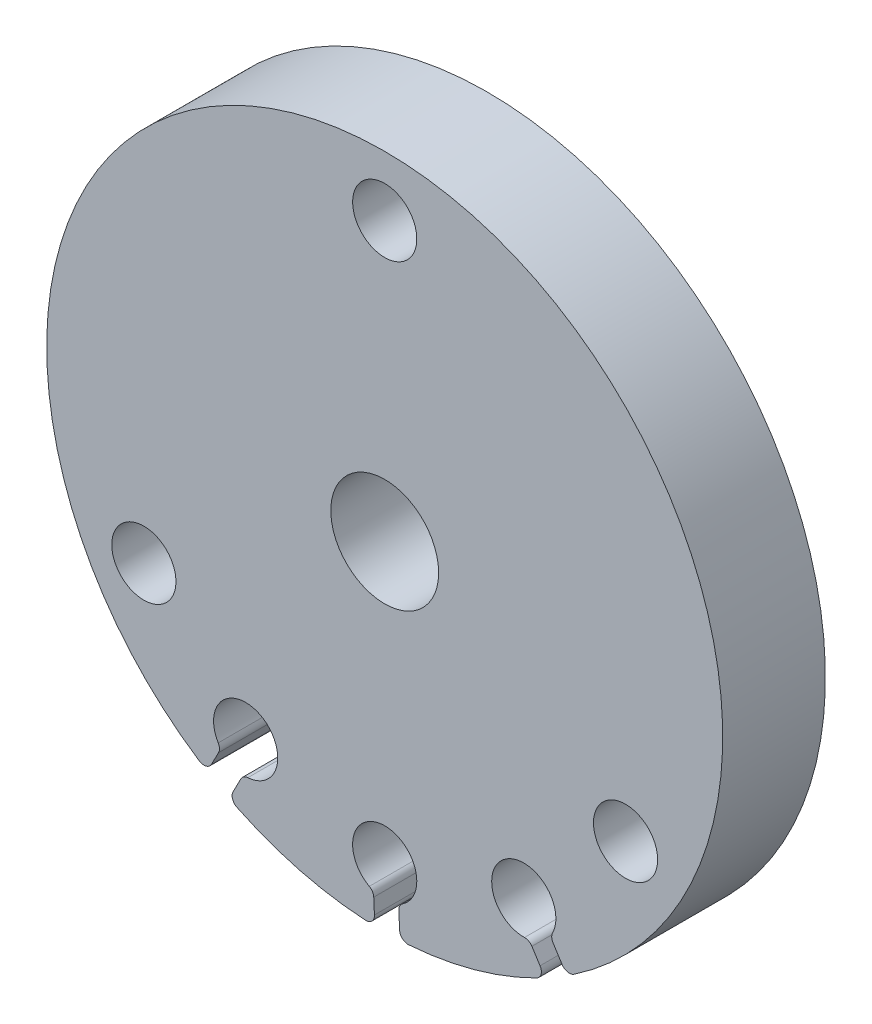
SolidWorks part; units mm, degrees
material "Полиэфирэфиркетон (ПЭЭК)"
ref_plane "Спереди" through (0, 0, 0) normal (0, 0, 1) x (1, 0, 0)
ref_plane "Сверху" through (0, 0, 0) normal (0, 1, 0) x (1, 0, 0)
ref_plane "Справа" through (0, 0, 0) normal (1, 0, 0) x (0, 0, -1)
sketch "Эскиз1" plane through (0, 0, 0) normal (0, 0, 1) x (1, 0, 0)
  circle A0 centre (0, 0) radius 19.75
  circle A1 centre (0, 0) radius 3.15
  dimension "D1" = 6.3
  dimension "D2" = 39.5
extrude "Бобышка-Вытянуть1" add sketch "Эскиз1" along normal blind 6
sketch "Эскиз2" plane through (0, 0, 0) normal (0, 0, -1) x (-1, 0, 0)
  line L0 (-10.9644, -17.1516) -> (-9.6728, -15.1312)
  line L2 (-8.4358, -15.922) -> (-9.6979, -17.8963)
  line L3 (-10.9644, -17.1516) -> (-9.6979, -17.8963)
  line L4 (-18.0712, -9.3715) -> (-15.9425, -8.2676) [skipped]
  line L5 (-18.0712, -9.3715) -> (-17.3468, -10.6497) [skipped]
  line L6 (-15.2666, -9.571) -> (-17.3468, -10.6497) [skipped]
  line L8 (-20.3359, 0.9196) -> (-17.9404, 0.8113) [skipped]
  line L9 (-20.3359, 0.9196) -> (-20.3476, -0.5495) [skipped]
  line L10 (-18.0067, -0.6554) -> (-20.3476, -0.5495) [skipped]
  line L12 (-17.1516, 10.9644) -> (-15.1312, 9.6728) [skipped]
  line L13 (-17.1516, 10.9644) -> (-17.8963, 9.6979) [skipped]
  line L14 (-15.922, 8.4358) -> (-17.8963, 9.6979) [skipped]
  line L16 (-9.3715, 18.0712) -> (-8.2676, 15.9425) [skipped]
  line L17 (-9.3715, 18.0712) -> (-10.6497, 17.3468) [skipped]
  line L18 (-9.571, 15.2666) -> (-10.6497, 17.3468) [skipped]
  line L20 (0.9196, 20.3359) -> (0.8113, 17.9404) [skipped]
  line L21 (0.9196, 20.3359) -> (-0.5495, 20.3476) [skipped]
  line L22 (-0.6554, 18.0067) -> (-0.5495, 20.3476) [skipped]
  line L24 (10.9644, 17.1516) -> (9.6728, 15.1312) [skipped]
  line L25 (10.9644, 17.1516) -> (9.6979, 17.8963) [skipped]
  line L26 (8.4358, 15.922) -> (9.6979, 17.8963) [skipped]
  line L28 (18.0712, 9.3715) -> (15.9425, 8.2676) [skipped]
  line L29 (18.0712, 9.3715) -> (17.3468, 10.6497) [skipped]
  line L30 (15.2666, 9.571) -> (17.3468, 10.6497) [skipped]
  line L32 (20.3359, -0.9196) -> (17.9404, -0.8113) [skipped]
  line L33 (20.3359, -0.9196) -> (20.3476, 0.5495) [skipped]
  line L34 (18.0067, 0.6554) -> (20.3476, 0.5495) [skipped]
  line L36 (17.1516, -10.9644) -> (15.1312, -9.6728) [skipped]
  line L37 (17.1516, -10.9644) -> (17.8963, -9.6979) [skipped]
  line L38 (15.922, -8.4358) -> (17.8963, -9.6979) [skipped]
  line L40 (9.3715, -18.0712) -> (8.2676, -15.9425)
  line L41 (9.3715, -18.0712) -> (10.6497, -17.3468)
  line L42 (9.571, -15.2666) -> (10.6497, -17.3468)
  line L44 (-0.9196, -20.3359) -> (-0.8113, -17.9404)
  line L45 (-0.9196, -20.3359) -> (0.5495, -20.3476)
  line L46 (0.6554, -18.0067) -> (0.5495, -20.3476)
  arc A0 (0.6554, -18.0067) -> (-0.8113, -17.9404) centre (0, -16.25) ccw
  arc A2 (-8.4358, -15.922) -> (-9.6728, -15.1312) centre (-8.125, -14.0729) ccw
  circle A3 centre (-14.0729, -8.125) radius 1.875
  circle A4 centre (-16.25, 0) radius 1.875 [skipped]
  circle A5 centre (-14.0729, 8.125) radius 1.875 [skipped]
  circle A6 centre (-8.125, 14.0729) radius 1.875 [skipped]
  circle A7 centre (0, 16.25) radius 1.875
  circle A8 centre (8.125, 14.0729) radius 1.875 [skipped]
  circle A9 centre (14.0729, 8.125) radius 1.875 [skipped]
  circle A10 centre (16.25, 0) radius 1.875 [skipped]
  circle A11 centre (14.0729, -8.125) radius 1.875
  arc A12 (9.571, -15.2666) -> (8.2676, -15.9425) centre (8.125, -14.0729) ccw
  point P27 (0, 0)
  point P78 (0, 0)
  dimension "D1" = 12
  dimension "D2" = 12
extrude "Вырез-Вытянуть2" cut sketch "Эскиз2" against normal through all
fillet "Скругление1" radius 0.5 12 edges at (-9.571, -15.2666, 3) (-10.3704, -16.8082, 3) (-8.2676, -15.9425, 3) (-9.0922, -17.5326, 3) (0.8113, -17.9404, 3) (0.8922, -19.7298, 3) (-0.6554, -18.0067, 3) (-0.577, -19.7416, 3) (8.4358, -15.922, 3) (9.3711, -17.3852, 3) (9.6728, -15.1312, 3) (10.6376, -16.6404, 3)
